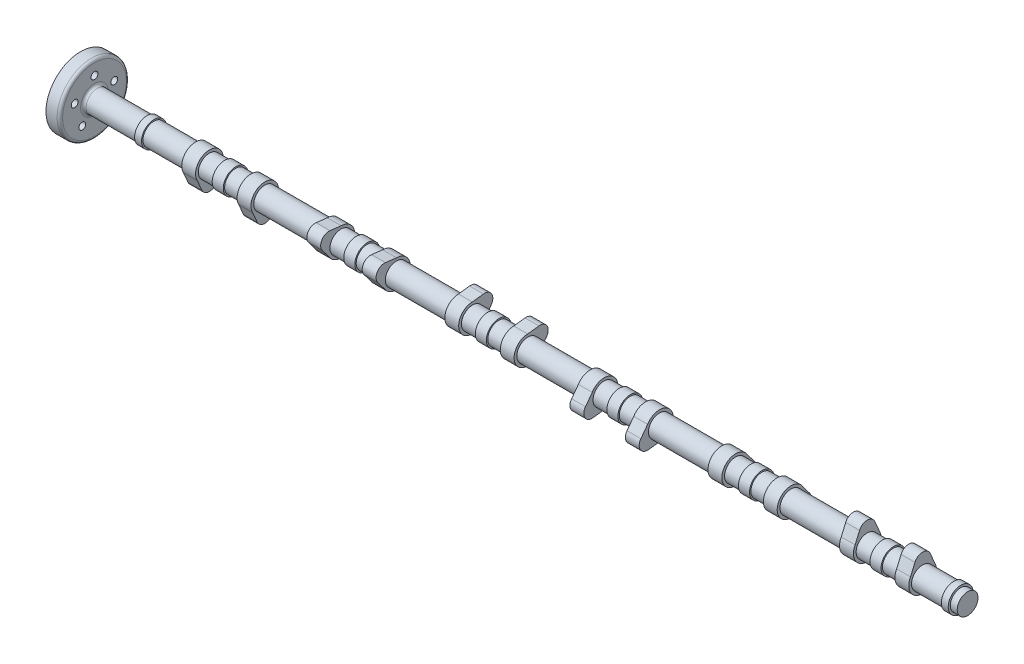
SolidWorks part; units mm, degrees
ref_plane "Plano frontal" through (0, 0, 0) normal (0, 0, 1) x (1, 0, 0)
ref_plane "Plano superior" through (0, 0, 0) normal (0, 1, 0) x (1, 0, 0)
ref_plane "Plano direito" through (0, 0, 0) normal (1, 0, 0) x (0, 0, -1)
sketch "Sketch1" plane through (0, 0, 0) normal (1, 0, 0) x (0, 0, -1)
  circle A0 centre (0, 0) radius 8
  dimension "D1" = 16
extrude "Boss-Extrude1" add sketch "Sketch1" along normal mid plane 95
sketch "Sketch2" plane through (0, 0, 0) normal (1, 0, 0) x (0, 0, -1)
  line L0 (0, 0) -> (-8.7462, -4.8481) construction
  line L1 (0, 0) -> (8.7462, -4.8481) construction
  line L2 (0, 0) -> (0, -16) construction
  line L3 (-8.7462, -4.8481) -> (-5.5407, -12.3434)
  line L4 (8.7462, -4.8481) -> (5.5407, -12.3434)
  arc A0 (8.7462, -4.8481) -> (-8.7462, -4.8481) centre (0, 0) ccw
  arc A1 (-5.5407, -12.3434) -> (5.5407, -12.3434) centre (0, -9.9738) ccw
  point P7 (0, -16)
  point P9 (0, 0)
  dimension "D1" = 20
  dimension "D2" = 122
  dimension "D3" = 16
extrude "Boss-Extrude2" add sketch "Sketch2" along normal blind 10 from offset 15
mirror "Mirror1" about plane through (0, 0, 0) normal (1, 0, 0) of "Boss-Extrude2"
sketch "Sketch3" plane through (0, 0, 0) normal (1, 0, 0) x (0, 0, -1)
  circle A0 centre (0, 0) radius 9
  dimension "D1" = 18
extrude "Boss-Extrude3" add sketch "Sketch3" along normal mid plane 8
pattern_linear "LPattern1" count 6 spacing 95 along (1, 0, 0) of bodies 104
move or copy body "Body-Move/Copy1" bodies to move or copy 107 copy no rotation origin (0, 0, 0) rotation axis (-1, 0, 0) rotation angle 60
move or copy body "Body-Move/Copy3" bodies to move or copy 105 copy no rotation origin (0, 0, 0) rotation axis (-1, 0, 0) rotation angle 120
move or copy body "Body-Move/Copy4" bodies to move or copy 108 copy no rotation origin (0, 0, 0) rotation axis (1, 0, 0) rotation angle 60
move or copy body "Body-Move/Copy5" bodies to move or copy 106 copy no rotation origin (0, 0, 0) rotation axis (1, 0, 0) rotation angle 120
move or copy body "Body-Move/Copy6" bodies to move or copy 109 copy no rotation origin (0, 0, 0) rotation axis (1, 0, 0) rotation angle 180
sketch "Sketch4" plane through (522.5, 0, 0) normal (1, 0, 0) x (0, 0, -1)
  circle A0 centre (0, 0) radius 9
  dimension "D1" = 18
extrude "Boss-Extrude4" add sketch "Sketch4" along normal blind 5
combine bodies "Combine1" operation type add bodies to combine 116 110 113 114 112 104
sketch "Sketch5" plane through (527.5, 0, 0) normal (1, 0, 0) x (0, 0, -1)
  circle A0 centre (0, 0) radius 7.5
  dimension "D1" = 15
extrude "Boss-Extrude5" add sketch "Sketch5" along normal blind 5
sketch "Sketch6" plane through (-47.5, 0, 0) normal (-1, 0, 0) x (0, 0, 1)
  circle A1 centre (0, 0) radius 8
  circle A2 centre (0, 0) radius 8
  dimension "D1" = 0
extrude "Boss-Extrude6" add sketch "Sketch6" along normal blind 7.5
sketch "Sketch7" plane through (-55, 0, 0) normal (-1, 0, 0) x (0, 0, 1)
  circle A0 centre (0, 0) radius 9
  dimension "D1" = 18
extrude "Boss-Extrude7" add sketch "Sketch7" along normal blind 5
sketch "Sketch8" plane through (-60, 0, 0) normal (-1, 0, 0) x (0, 0, 1)
  circle A0 centre (0, 0) radius 8
  dimension "D1" = 16
extrude "Boss-Extrude8" add sketch "Sketch8" along normal blind 38
sketch "Sketch10" plane through (-98, 0, 0) normal (-1, 0, 0) x (0, 0, 1)
  circle A0 centre (0, 0) radius 2.5
  circle A1 centre (0, 0) radius 25
  dimension "D1" = 5
  dimension "D2" = 50
extrude "Boss-Extrude9" add sketch "Sketch10" along normal blind 10
sketch "Sketch11" plane through (-108, 0, 0) normal (-1, 0, 0) x (0, 0, 1)
  circle A0 centre (0, 0) radius 15 construction
  circle A1 centre (0, 0) radius 2.5
  circle A2 centre (0, 15) radius 2.5
  circle A3 centre (14.2658, 4.6353) radius 2.5
  circle A4 centre (8.8168, -12.1353) radius 2.5
  circle A5 centre (-8.8168, -12.1353) radius 2.5
  circle A6 centre (-14.2658, 4.6353) radius 2.5
  point P16 (0, 0)
  dimension "D1" = 30
  dimension "D2" = 5
  dimension "D3" = 5
extrude "Cut-Extrude1" cut sketch "Sketch11" against normal blind 15
fillet "Fillet1" radius 2 2 edges at (-98, 0, 25) (-98, 0, 8)
